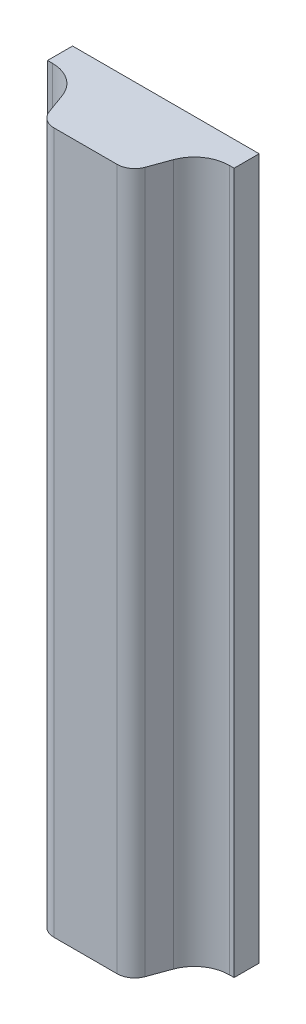
SolidWorks part; units mm, degrees
ref_plane "前视基准面" through (0, 0, 0) normal (0, 0, 1) x (1, 0, 0)
ref_plane "上视基准面" through (0, 0, 0) normal (0, 1, 0) x (1, 0, 0)
ref_plane "右视基准面" through (0, 0, 0) normal (1, 0, 0) x (0, 0, -1)
other "Configuration Table"
sketch "草图1" plane through (0, 0, 0) normal (0, 1, 0) x (1, 0, 0)
  line L0 (4.1811, -0.3462) -> (4.2666, -0.1111)
  line L1 (3.0853, -0.3462) -> (2.9997, -0.1111)
  line L2 (2.5685, 0.4376) -> (2.5685, 0.1521)
  line L3 (4.6978, 0.4376) -> (2.5685, 0.4376)
  line L4 (4.6978, 0.1521) -> (4.6978, 0.4376)
  line L5 (3.2732, -0.4777) -> (3.9931, -0.4777)
  line L6 (4.6425, 0.1521) -> (4.6978, 0.1521)
  line L7 (2.6238, 0.1521) -> (2.5685, 0.1521)
  arc A0 (3.9931, -0.4777) -> (4.1811, -0.3462) centre (3.9931, -0.2777) ccw
  arc A1 (3.0853, -0.3462) -> (3.2732, -0.4777) centre (3.2732, -0.2777) ccw
  arc A2 (2.9997, -0.1111) -> (2.6238, 0.1521) centre (2.6238, -0.2479) ccw
  arc A3 (4.6425, 0.1521) -> (4.2666, -0.1111) centre (4.6425, -0.2479) ccw
extrude "凸台-拉伸1" add sketch "草图1" along normal blind 8
sketch "草图2" plane through (0, 0, -0.4376) normal (0, 0, -1) x (-1, 0, 0)
  line L0 (-3.6332, 8) -> (-3.6332, 0)
  line L1 (-4.6978, 8) -> (-2.5685, 8) construction
  line L2 (-4.6978, 0) -> (-2.5685, 0) construction
sketch "草图4" plane through (0, 8, 0) normal (0, 1, 0) x (1, 0, 0)
  line L0 (2.5685, 0.4376) -> (4.6978, 0.4376)
  line L1 (2.5685, 0.4376) -> (2.5685, 0.1521) construction
  line L2 (4.6978, 0.1521) -> (4.6978, 0.4376) construction
  line L3 (4.6978, 0.4376) -> (2.5685, 0.4376) construction
